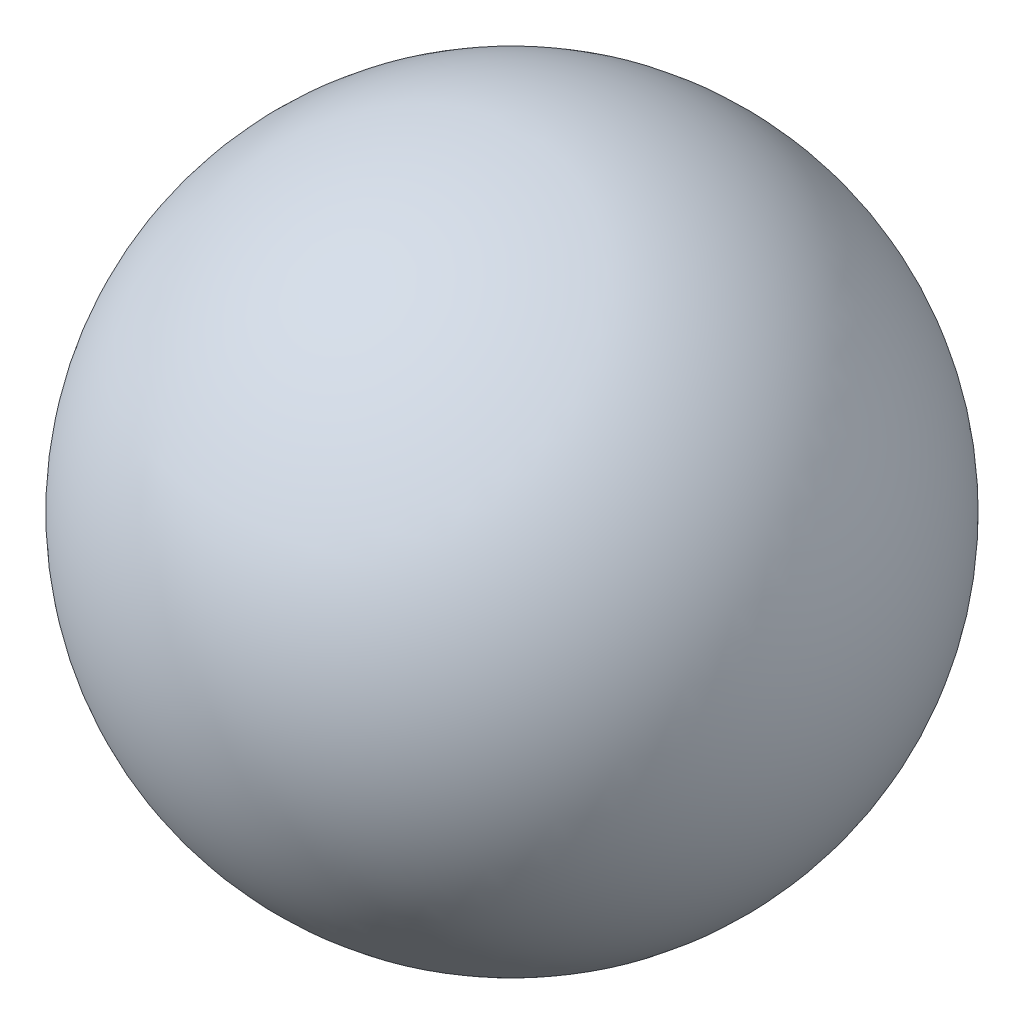
SolidWorks part; units mm, degrees
ref_plane "Front Plane" through (0, 0, 0) normal (0, 0, 1) x (1, 0, 0)
ref_plane "Top Plane" through (0, 0, 0) normal (0, 1, 0) x (1, 0, 0)
ref_plane "Right Plane" through (0, 0, 0) normal (1, 0, 0) x (0, 0, -1)
sketch "Sketch1" plane through (0, 0, 0) normal (0, 0, 1) x (1, 0, 0)
  line L0 (0, 0) -> (0, 53.5105) construction
  line L1 (0, 0) -> (0, -49.811) construction
  line L5 (0, 36.1152) -> (0, -36.1152)
  arc A3 (0, 36.1152) -> (0, -36.1152) centre (0, 0) cw
revolve "Revolve6" add sketch "Sketch1" angle 360 about L0
